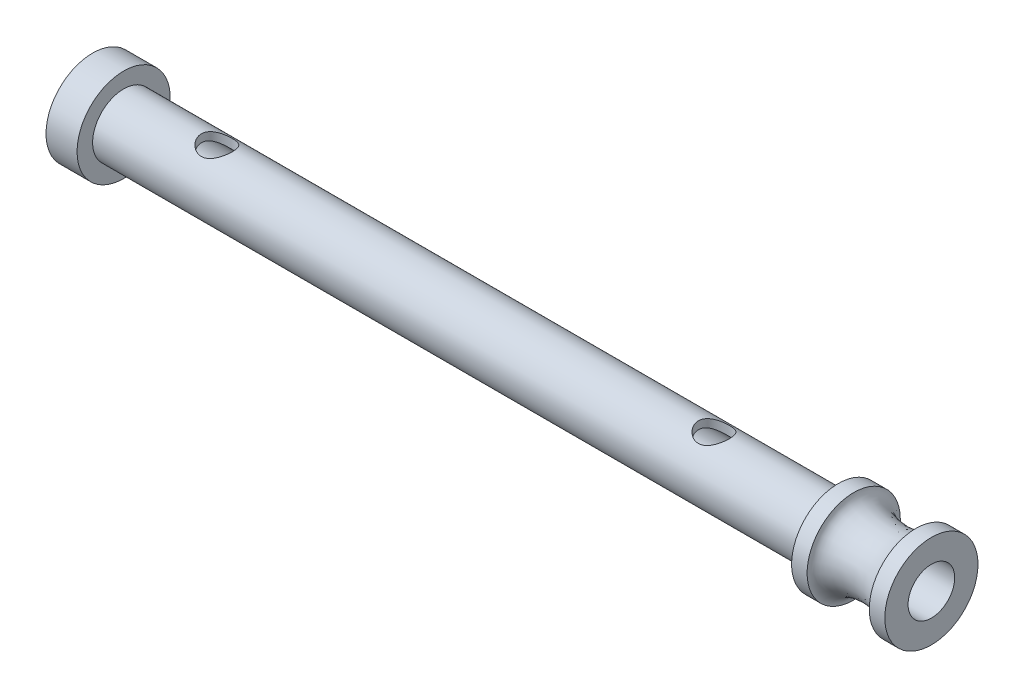
SolidWorks part; units mm, degrees
ref_plane "Alzado" through (0, 0, 0) normal (0, 0, 1) x (1, 0, 0)
ref_plane "Planta" through (0, 0, 0) normal (0, 1, 0) x (1, 0, 0)
ref_plane "Vista lateral" through (0, 0, 0) normal (1, 0, 0) x (0, 0, -1)
sketch "Croquis1" plane through (0, 0, 0) normal (1, 0, 0) x (0, 0, -1)
  circle A0 centre (0, 0) radius 10
  circle A1 centre (0, 0) radius 7.5
  dimension "D1" = 20
  dimension "D2" = 15
extrude "Saliente-Extruir1" add sketch "Croquis1" along normal mid plane 260
sketch "Croquis2" plane through (-130, 0, 0) normal (-1, 0, 0) x (0, 0, 1)
  circle A0 centre (0, 0) radius 15
  circle A1 centre (0, 0) radius 7.5
  dimension "D1" = 30
extrude "Saliente-Extruir2" add sketch "Croquis2" along normal blind 10
sketch "Croquis3" plane through (0, 0, 0) normal (0, 1, 0) x (1, 0, 0)
  line L0 (-130, -10) -> (-130, 10) construction
  circle A0 centre (-100, 0) radius 5
  circle A1 centre (60, 0) radius 5
  point P4 (0, 0)
  point P9 (0, 0)
  dimension "D1" = 10
  dimension "D2" = 30
  dimension "D3" = 160
extrude "Cortar-Extruir1" cut sketch "Croquis3" against normal through all both and the other way through all
sketch "Croquis4" plane through (130, 0, 0) normal (1, 0, 0) x (0, 0, -1)
  circle A1 centre (0, 0) radius 15
  circle A2 centre (0, 0) radius 10
  circle A3 centre (0, 0) radius 10
  dimension "D1" = 0
extrude "Saliente-Extruir3" add sketch "Croquis4" against normal blind 30
sketch "Croquis5" plane through (0, 0, 0) normal (0, 0, 1) x (1, 0, 0)
  line L1 (130, 15) -> (100, 15) construction
  line L2 (130, 0) -> (-6.6637, 0) construction
  ellipse E0 centre (115, 15) end of major axis (105, 15) minor radius 5
  dimension "D1" = 10
  dimension "D2" = 20
revolve "Cortar-Revolución1" cut sketch "Croquis5" angle 360 about L2
